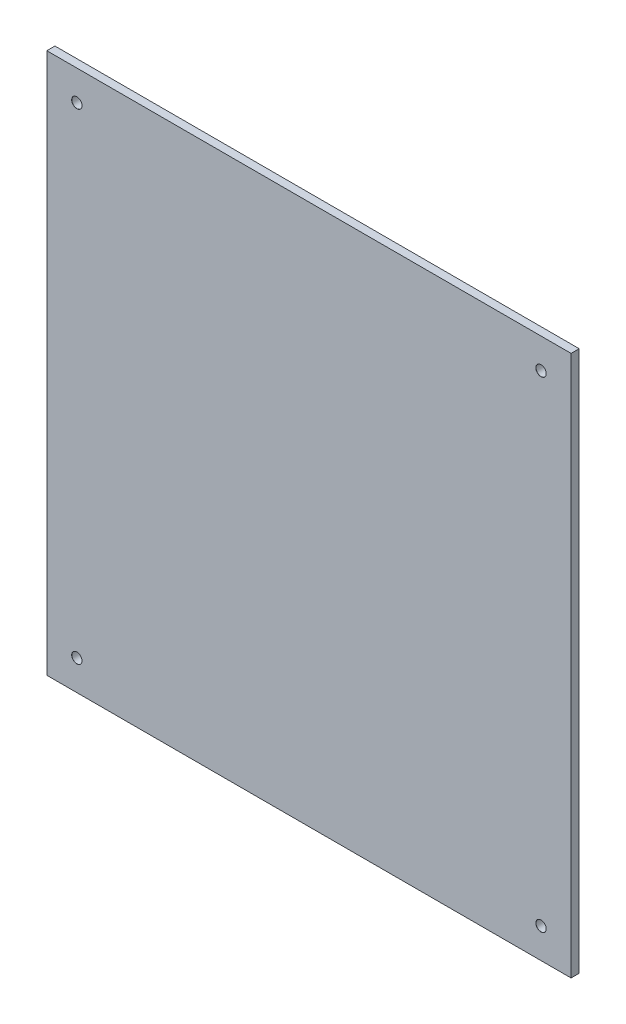
SolidWorks part; units mm, degrees
ref_plane "Front Plane" through (0, 0, 0) normal (0, 0, 1) x (1, 0, 0)
ref_plane "Top Plane" through (0, 0, 0) normal (0, 1, 0) x (1, 0, 0)
ref_plane "Right Plane" through (0, 0, 0) normal (1, 0, 0) x (0, 0, -1)
sketch "Sketch1" plane through (0, 0, 0) normal (0, 0, 1) x (1, 0, 0)
  line L1 (250, 10) -> (75.5427, 10)
  line L2 (250, 10) -> (250, -170)
  line L3 (250, -170) -> (75.5427, -170)
  line L4 (75.5427, 10) -> (75.5427, -170)
extrude "Boss-Extrude1" add sketch "Sketch1" along normal blind 2.7
hole_wizard "M3 Clearance Hole1" positions "3DSketch1" profile "Sketch2" hole size "M3" standard "ANSI Metric" end condition through all
sketch3d "3DSketch1"
  line L0 (75.5427, 10, 2.7) -> (75.5427, -170, 2.7) construction
  line L1 (250, -170, 2.7) -> (250, 10, 2.7) construction
  line L2 (250, 10, 2.7) -> (75.5427, 10, 2.7) construction
  line L3 (75.5427, -170, 2.7) -> (250, -170, 2.7) construction
  point P0 (85.5427, 0, 2.7)
  point P2 (85.5427, -160, 2.7)
  point P4 (240, -160, 2.7)
  point P6 (240, 0, 2.7)
  dimension "D1" = 10
  dimension "D2" = 10
  dimension "D3" = 10
  dimension "D4" = 10
  dimension "D5" = 10
  dimension "D6" = 10
  dimension "D7" = 10
  dimension "D8" = 10
sketch "Sketch2" plane through (85.5427, 0, 2.7) normal (1, 0, 0) x (0, -1, 0)
  line L0 (0, 0) -> (0, 2.7)
  line L1 (0, 2.7) -> (1.7, 2.7)
  line L2 (1.7, 2.7) -> (1.7, 0.025)
  line L3 (1.7, 0.025) -> (1.725, 0)
  line L5 (1.725, 0) -> (0, 0)
  line L6 (-1.7, 0.025) -> (-1.725, 0) construction
  line L11 (0, -6.35) -> (0, 107.95) construction
  dimension "Thru Hole Dia." = 3.4
  dimension "Thru Hole Depth" = 2.7
  dimension "Near C'Sink Dia." = 3.45
  dimension "Near C'Sink Angle" = 90
